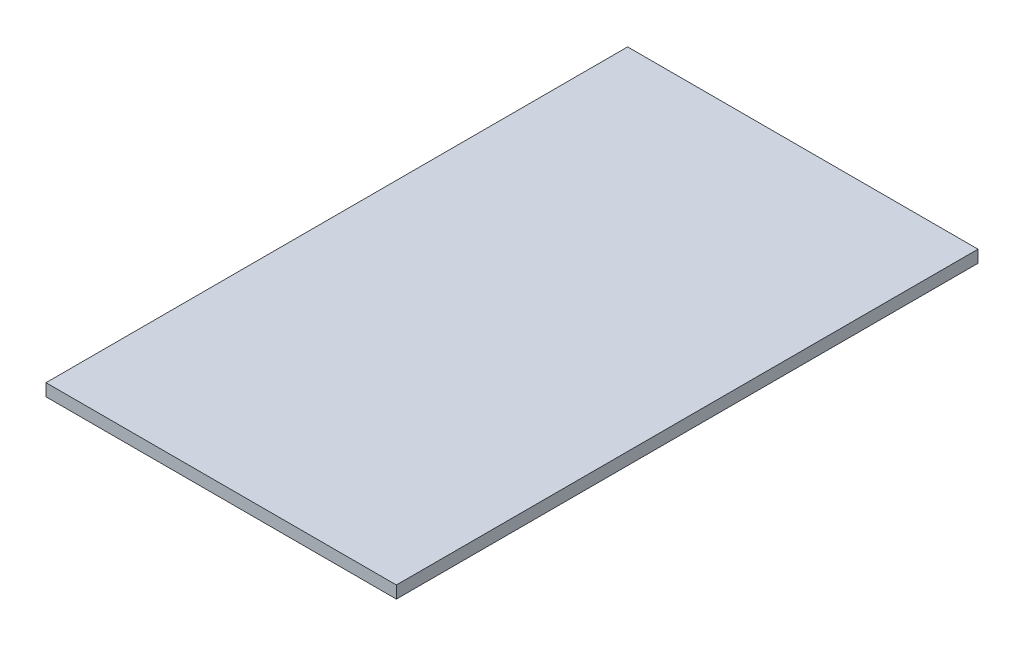
SolidWorks part; units mm, degrees
ref_plane "Front Plane" through (0, 0, 0) normal (0, 0, 1) x (1, 0, 0)
ref_plane "Top Plane" through (0, 0, 0) normal (0, 1, 0) x (1, 0, 0)
ref_plane "Right Plane" through (0, 0, 0) normal (1, 0, 0) x (0, 0, -1)
sketch "Sketch1" plane through (0, 0, 0) normal (0, 1, 0) x (1, 0, 0)
  line L1 (-50, -83) -> (50, -83)
  line L2 (-50, -83) -> (-50, 83)
  line L3 (-50, 83) -> (50, 83)
  line L4 (50, -83) -> (50, 83)
  line L5 (-50, -83) -> (50, 83) construction
  line L6 (-50, 83) -> (50, -83) construction
  point P0 (0, 0)
  dimension "D1" = 166
  dimension "D2" = 100
extrude "MAIN BODY" add sketch "Sketch1" along normal blind 3.5
sketch "Sketch2" plane through (0, 0, 0) normal (0, -1, 0) x (1, 0, 0)
  line L0 (50, -83) -> (-50, -83) construction
  line L1 (-46, -83) -> (26, -83)
  line L2 (-46, -83) -> (-46, -43)
  line L3 (-46, -43) -> (26, -43)
  line L4 (26, -83) -> (26, -43)
  line L5 (-50, -83) -> (-50, 83) construction
  line L6 (50, 83) -> (50, -83) construction
  dimension "D1" = 4
  dimension "D2" = 24
  dimension "D3" = 40
extrude "PCBs AND SUCH" add sketch "Sketch2" along normal blind 5
